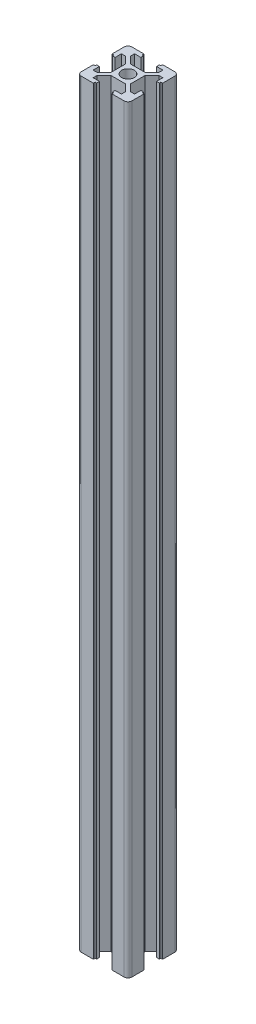
SolidWorks part; units mm, degrees
ref_plane "前视基准面" through (0, 0, 0) normal (0, 0, 1) x (1, 0, 0)
ref_plane "上视基准面" through (0, 0, 0) normal (0, 1, 0) x (1, 0, 0)
ref_plane "右视基准面" through (0, 0, 0) normal (1, 0, 0) x (0, 0, -1)
sketch "草图1" plane through (0, 0, 0) normal (0, 1, 0) x (1, 0, 0)
  line L0 (-10, 0) -> (10, 0) construction
  line L2 (10, 10) -> (3.65, 10)
  line L4 (-3.65, 10) -> (-3.65, 9.3033)
  line L5 (-3.65, 9.3033) -> (-3.1, 9.3033)
  line L6 (-3.1, 9.3033) -> (-3.1, 8.2)
  line L7 (-3.1, 8.2) -> (-5.6, 8.2)
  line L8 (-5.6, 8.2) -> (-5.6, 6.6607)
  line L9 (-5.6, 6.6607) -> (-2.8393, 3.9)
  line L11 (5.6, 6.6607) -> (5.6, 8.2)
  line L12 (5.6, 8.2) -> (3.1, 8.2)
  line L13 (3.1, 8.2) -> (3.1, 9.3033)
  line L14 (3.1, 9.3033) -> (3.65, 9.3033)
  line L15 (3.65, 9.3033) -> (3.65, 10)
  line L16 (-3.65, 10) -> (-10, 10)
  line L17 (0, 0) -> (0, 16.5896) construction
  line L18 (-2.8393, 3.9) -> (2.8393, 3.9)
  line L19 (2.8393, 3.9) -> (5.6, 6.6607)
  line L20 (10, -10) -> (10, -3.65)
  line L21 (10, 3.65) -> (9.3033, 3.65)
  line L22 (9.3033, 3.65) -> (9.3033, 3.1)
  line L23 (9.3033, 3.1) -> (8.2, 3.1)
  line L24 (8.2, 3.1) -> (8.2, 5.6)
  line L25 (8.2, 5.6) -> (6.6607, 5.6)
  line L26 (6.6607, 5.6) -> (3.9, 2.8393)
  line L27 (6.6607, -5.6) -> (8.2, -5.6)
  line L28 (8.2, -5.6) -> (8.2, -3.1)
  line L29 (8.2, -3.1) -> (9.3033, -3.1)
  line L30 (9.3033, -3.1) -> (9.3033, -3.65)
  line L31 (9.3033, -3.65) -> (10, -3.65)
  line L32 (10, 3.65) -> (10, 10)
  line L33 (3.9, 2.8393) -> (3.9, -2.8393)
  line L34 (3.9, -2.8393) -> (6.6607, -5.6)
  line L35 (0, 10) -> (0, -10) construction
  line L36 (0, 0) -> (16.5896, 0) construction
  line L37 (-10, -10) -> (-3.65, -10)
  line L38 (3.65, -10) -> (3.65, -9.3033)
  line L39 (3.65, -9.3033) -> (3.1, -9.3033)
  line L40 (3.1, -9.3033) -> (3.1, -8.2)
  line L41 (3.1, -8.2) -> (5.6, -8.2)
  line L42 (5.6, -8.2) -> (5.6, -6.6607)
  line L43 (5.6, -6.6607) -> (2.8393, -3.9)
  line L44 (-5.6, -6.6607) -> (-5.6, -8.2)
  line L45 (-5.6, -8.2) -> (-3.1, -8.2)
  line L46 (-3.1, -8.2) -> (-3.1, -9.3033)
  line L47 (-3.1, -9.3033) -> (-3.65, -9.3033)
  line L48 (-3.65, -9.3033) -> (-3.65, -10)
  line L49 (3.65, -10) -> (10, -10)
  line L50 (2.8393, -3.9) -> (-2.8393, -3.9)
  line L51 (-2.8393, -3.9) -> (-5.6, -6.6607)
  line L52 (10, 0) -> (-10, 0) construction
  line L53 (0, 0) -> (0, -16.5896) construction
  line L54 (-10, 10) -> (-10, 3.65)
  line L55 (-10, -3.65) -> (-9.3033, -3.65)
  line L56 (-9.3033, -3.65) -> (-9.3033, -3.1)
  line L57 (-9.3033, -3.1) -> (-8.2, -3.1)
  line L58 (-8.2, -3.1) -> (-8.2, -5.6)
  line L59 (-8.2, -5.6) -> (-6.6607, -5.6)
  line L60 (-6.6607, -5.6) -> (-3.9, -2.8393)
  line L61 (-6.6607, 5.6) -> (-8.2, 5.6)
  line L62 (-8.2, 5.6) -> (-8.2, 3.1)
  line L63 (-8.2, 3.1) -> (-9.3033, 3.1)
  line L64 (-9.3033, 3.1) -> (-9.3033, 3.65)
  line L65 (-9.3033, 3.65) -> (-10, 3.65)
  line L66 (-10, -3.65) -> (-10, -10)
  line L67 (-3.9, -2.8393) -> (-3.9, 2.8393)
  line L68 (-3.9, 2.8393) -> (-6.6607, 5.6)
  line L69 (0, -10) -> (0, 10) construction
  line L70 (0, 0) -> (-16.5896, 0) construction
  circle A0 centre (0, 0) radius 2.5
  point P12 (0, 3.9)
  dimension "D8" = 1.5
  dimension "D10" = 5
  dimension "D1" = 20
  dimension "D2" = 10
  dimension "D3" = 7.3
  dimension "D4" = 6.2
  dimension "D5" = 1.8
  dimension "D6" = 4.3
  dimension "D7" = 11.2
  dimension "D9" = 4
extrude "凸台-拉伸1" add sketch "草图1" along normal blind 300
fillet "圆角1" radius 1.5 4 edges at (-10, 150, 10) (-10, 150, -10) (10, 150, 10) (10, 150, -10)
